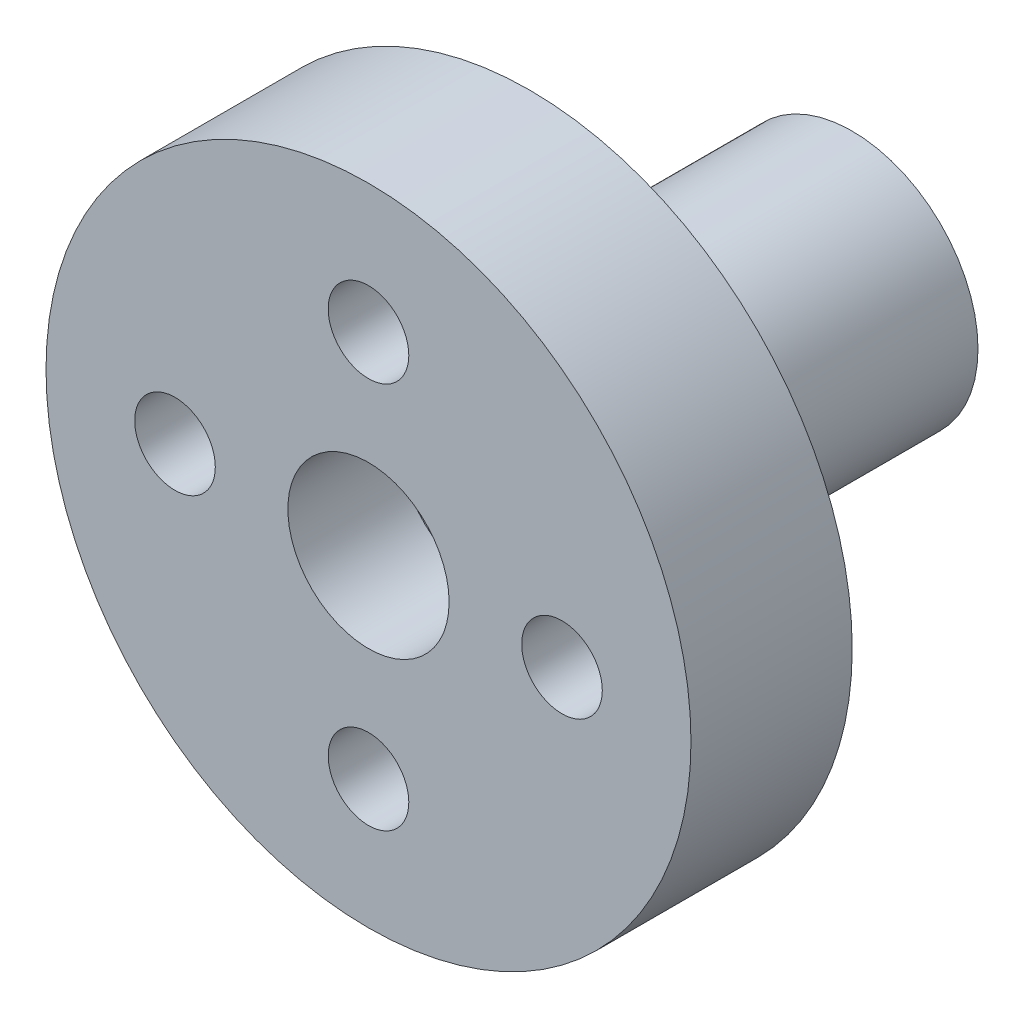
SolidWorks part; units mm, degrees
ref_plane "前视基准面" through (0, 0, 0) normal (0, 0, 1) x (1, 0, 0)
ref_plane "上视基准面" through (0, 0, 0) normal (0, 1, 0) x (1, 0, 0)
ref_plane "右视基准面" through (0, 0, 0) normal (1, 0, 0) x (0, 0, -1)
sketch "草图1" plane through (0, 0, 0) normal (0, 0, 1) x (1, 0, 0)
  circle A0 centre (0, 51.7783) radius 2.65
  circle A1 centre (0, 51.7783) radius 3.9
  dimension "D1" = 5.3
  dimension "D2" = 7.8
extrude "凸台-拉伸1" add sketch "草图1" along normal blind 10
sketch "草图2" plane through (0, 0, 10) normal (0, 0, 1) x (1, 0, 0)
  circle A3 centre (0, 51.7783) radius 3.9
  circle A4 centre (0, 51.7783) radius 3.9
  circle A6 centre (0, 51.7783) radius 2.65
  circle A7 centre (0, 51.7783) radius 2.65 construction
  dimension "D2" = 0
sketch "草图3" plane through (0, 0, 10) normal (0, 0, 1) x (1, 0, 0)
  circle A0 centre (0, 51.7783) radius 10
  dimension "D1" = 20
extrude "凸台-拉伸2" add sketch "草图3" along normal blind 5
sketch "草图5" plane through (0, 0, 15) normal (0, 0, 1) x (1, 0, 0)
  line L0 (-10, 51.7783) -> (10, 51.7783) construction
  line L1 (0, 57.7783) -> (0, 45.7783) construction
  circle A0 centre (6, 51.7783) radius 1.25
  circle A5 centre (0, 57.7783) radius 1.25
  circle A6 centre (0, 51.7783) radius 10
  circle A7 centre (0, 51.7783) radius 10
  circle A8 centre (0, 45.7783) radius 1.25
  circle A9 centre (-6, 51.7783) radius 1.25
  point P2 (0, 0)
  point P16 (0, 51.7783)
  dimension "D1" = 0
  dimension "D3" = 2.5
  dimension "D4" = 6
  dimension "D2" = 4
extrude "切除-拉伸1" cut sketch "草图5" against normal blind 3 contours A9 | A5 | A8 | A0
sketch "草图7" plane through (0, 0, 15) normal (0, 0, 1) x (1, 0, 0)
  circle A0 centre (0, 51.7783) radius 2.5
  dimension "D1" = 5
extrude "切除-拉伸2" cut sketch "草图7" against normal blind 3.5
